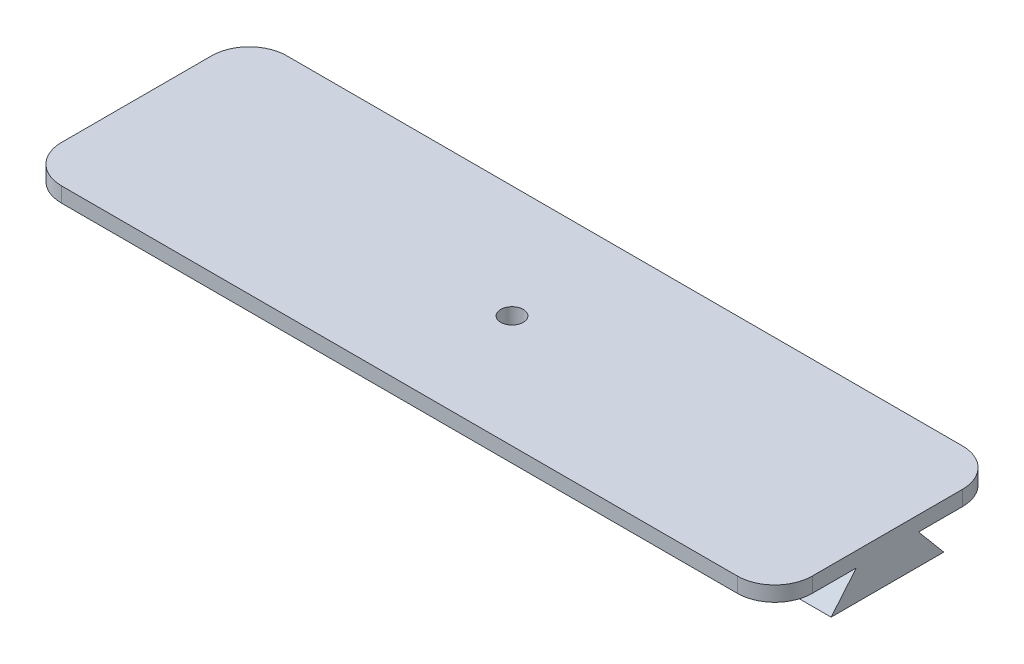
SolidWorks part; units mm, degrees
ref_plane "Front Plane" through (0, 0, 0) normal (0, 0, 1) x (1, 0, 0)
ref_plane "Top Plane" through (0, 0, 0) normal (0, 1, 0) x (1, 0, 0)
ref_plane "Right Plane" through (0, 0, 0) normal (1, 0, 0) x (0, 0, -1)
sketch "Sketch4" plane through (0, 0, 0) normal (0, 1, 0) x (1, 0, 0)
  line L1 (0, 0) -> (100, 0)
  line L2 (0, 0) -> (0, -30)
  line L3 (0, -30) -> (100, -30)
  line L4 (100, 0) -> (100, -30)
  dimension "D1" = 30
  dimension "D2" = 100
extrude "Boss-Extrude2" add sketch "Sketch4" along normal blind 6
sketch "Sketch6" plane through (100, 0, 0) normal (1, 0, 0) x (0, 0, -1)
  line L0 (-15, 6) -> (-15, 0) construction
  line L1 (-30, 6) -> (0, 6) construction
  line L2 (-30, 0) -> (0, 0) construction
  line L4 (-7.5, 0) -> (0, 0)
  line L6 (-22.5, 0) -> (-30, 0)
  line L12 (-30, 0) -> (-30, 4)
  line L13 (-30, 6) -> (-30, 0) construction
  line L14 (-30, 4) -> (-19.1436, 4)
  line L15 (-22.5, 0) -> (-19.1436, 4)
  line L16 (0, 0) -> (0, 4)
  line L17 (0, 4) -> (-10.8564, 4)
  line L18 (-7.5, 0) -> (-10.8564, 4)
  point P15 (0, 0)
  dimension "D1" = 4
  dimension "D2" = 50
  dimension "D3" = 15
  dimension "D4" = 4
  dimension "D5" = 8.2872
extrude "Cut-Extrude1" cut sketch "Sketch6" against normal through all
sketch "Sketch7" plane through (0, 6, 0) normal (0, 1, 0) x (1, 0, 0)
  line L0 (0, -15) -> (100, -15) construction
  line L1 (0, 0) -> (0, -30) construction
  line L2 (100, -30) -> (100, 0) construction
  circle A0 centre (50, -15) radius 1.5
  dimension "D1" = 3
extrude "Cut-Extrude2" cut sketch "Sketch7" against normal through all
fillet "Fillet2" radius 5 1 edges at (0, 5, 0)
fillet "Fillet3" radius 5 3 edges at (100, 5, 0) (100, 5, 30) (0, 5, 30)
